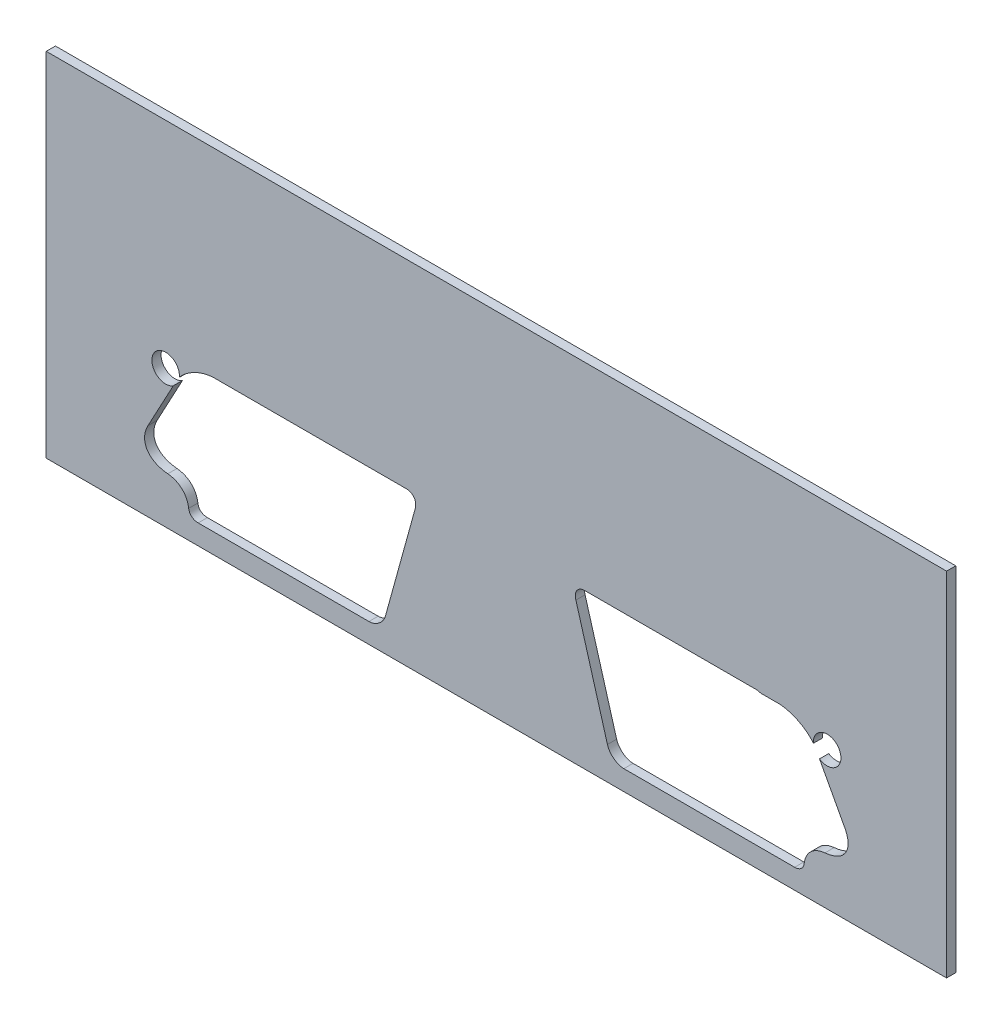
SolidWorks part; units mm, degrees
ref_plane "Спереди" through (0, 0, 0) normal (0, 0, 1) x (1, 0, 0)
ref_plane "Сверху" through (0, 0, 0) normal (0, 1, 0) x (1, 0, 0)
ref_plane "Справа" through (0, 0, 0) normal (1, 0, 0) x (0, 0, -1)
sketch "Эскиз1" plane through (0, 0, 0) normal (0, 0, 1) x (1, 0, 0)
  line L1 (-49, 5.8392) -> (-49, -22.5167)
  line L2 (-49, -22.5167) -> (49, -22.5167)
  line L3 (49, 5.8392) -> (49, -22.5167)
  line L6 (49, 26.4822) -> (49, 5.1962) construction
  line L8 (-49, 5.8392) -> (-49, 15.8392)
  line L9 (-49, 15.8392) -> (49, 15.8392)
  line L10 (49, 5.8392) -> (49, 15.8392)
extrude "Бобышка-Вытянуть1" add sketch "Эскиз1" along normal blind 1
sketch "Эскиз2" plane through (0, 0, 0) normal (0, 0, -1) x (-1, 0, 0)
  line L0 (27.2261, -9.1221) -> (15.7399, -9.1221)
  line L1 (14.9178, -10.1567) -> (17.4421, -18.9309)
  line L2 (19.1226, -20.331) -> (30.8268, -20.331)
  line L3 (31.6433, -19.2954) -> (29.101, -10.4886)
  line L4 (0, 0) -> (0, -19.7017) construction
  line L5 (-31.6433, -19.2954) -> (-29.101, -10.4886)
  line L6 (-19.1226, -20.331) -> (-30.8268, -20.331)
  line L7 (-14.9178, -10.1567) -> (-17.4421, -18.9309)
  line L8 (-27.2261, -9.1221) -> (-15.7399, -9.1221)
  arc A0 (15.7399, -9.1221) -> (14.9178, -10.1567) centre (15.8146, -10.0254) ccw
  arc A1 (17.4421, -18.9309) -> (19.1226, -20.331) centre (19.2232, -18.5017) ccw
  arc A2 (30.8268, -20.331) -> (31.6433, -19.2954) centre (30.7494, -19.4304) ccw
  arc A3 (29.101, -10.4886) -> (27.2261, -9.1221) centre (27.3312, -10.9473) ccw
  arc A4 (-29.101, -10.4886) -> (-27.2261, -9.1221) centre (-27.3312, -10.9473) cw
  arc A5 (-30.8268, -20.331) -> (-31.6433, -19.2954) centre (-30.7494, -19.4304) cw
  arc A6 (-17.4421, -18.9309) -> (-19.1226, -20.331) centre (-19.2232, -18.5017) cw
  arc A7 (-15.7399, -9.1221) -> (-14.9178, -10.1567) centre (-15.8146, -10.0254) cw
extrude "Вырез-Вытянуть4" cut sketch "Эскиз2" against normal through all
sketch "Эскиз4" plane through (0, 0, 0) normal (0, 0, -1) x (-1, 0, 0)
  circle A0 centre (36, -7.525) radius 1.5
  circle A1 centre (-36, -7.525) radius 1.5
extrude "Вырез-Вытянуть5" cut sketch "Эскиз4" against normal through all
sketch "Sketch3" plane through (0, 0, 1) normal (0, 0, 1) x (1, 0, 0)
  line L4 (-35.1709, -8.775) -> (-37.9251, -13.9067)
  line L5 (8.6523, -7.0681) -> (12.0857, -18.9615)
  line L6 (28.2287, -5.6825) -> (9.638, -5.6825)
  line L7 (30.6309, -5.7832) -> (28.7783, -5.7839)
  line L8 (37.9106, -13.8798) -> (35.1709, -8.775)
  line L9 (13.8713, -20.3472) -> (32.462, -20.3472)
  line L10 (8.6523, -7.0681) -> (12.0857, -18.9615)
  line L11 (28.2287, -5.6825) -> (9.638, -5.6825)
  line L12 (30.6309, -5.7832) -> (28.7783, -5.7839)
  line L13 (37.9106, -13.8798) -> (35.1709, -8.775)
  line L14 (13.8713, -20.3472) -> (32.462, -20.3472)
  line L15 (-9.8219, -5.7989) -> (-30.645, -5.807)
  line L16 (-12.0807, -18.9439) -> (-8.8308, -7.1669)
  line L17 (-32.462, -20.3472) -> (-13.8713, -20.3472)
  line L18 (-35.1709, -8.775) -> (-37.9251, -13.9067)
  line L19 (-9.8219, -5.7989) -> (-30.645, -5.807)
  line L20 (-12.0807, -18.9439) -> (-8.8308, -7.1669)
  line L21 (-32.462, -20.3472) -> (-13.8713, -20.3472)
  arc A2 (34.5043, -7.6389) -> (34.5716, -7.9829) centre (36, -7.525) ccw
  arc A3 (34.5716, -7.9829) -> (35.1709, -8.775) centre (36, -7.525) ccw
  arc A4 (34.5043, -7.6389) -> (34.5716, -7.9829) centre (36, -7.525) ccw
  arc A5 (34.5716, -7.9829) -> (35.1709, -8.775) centre (36, -7.525) ccw
  arc A6 (-35.1709, -8.775) -> (-34.5791, -8.0058) centre (-36, -7.525) ccw
  arc A7 (-34.5791, -8.0058) -> (-34.5051, -7.6482) centre (-36, -7.525) ccw
  arc A8 (-35.1709, -8.775) -> (-34.5791, -8.0058) centre (-36, -7.525) ccw
  arc A9 (-34.5791, -8.0058) -> (-34.5051, -7.6482) centre (-36, -7.525) ccw
  ellipse E5 centre (10.038, -7.0681) end of major axis (8.8285, -6.0207) minor radius 1.2 (9.638, -5.6825) -> (8.6523, -7.0681) ccw
  ellipse E6 centre (28.6287, -7.0681) end of major axis (27.4192, -6.0207) minor radius 1.2 (28.7783, -5.7839) -> (28.2287, -5.6825) ccw
  ellipse E7 centre (31.8702, -8.0919) end of major axis (28.7995, -6.6629) minor radius 2 (34.5043, -7.6389) -> (30.6309, -5.7832) ccw
  ellipse E8 centre (32.062, -18.9615) end of major axis (30.8525, -17.9141) minor radius 1.2 (32.462, -20.3472) -> (33.4962, -19.4843) ccw
  ellipse E9 centre (13.4713, -18.9615) end of major axis (12.2618, -17.9141) minor radius 1.2 (12.0857, -18.9615) -> (13.8713, -20.3472) ccw
  ellipse E10 centre (10.038, -7.0681) end of major axis (8.8285, -6.0207) minor radius 1.2 (9.638, -5.6825) -> (8.6523, -7.0681) ccw
  ellipse E11 centre (28.6287, -7.0681) end of major axis (27.4192, -6.0207) minor radius 1.2 (28.7783, -5.7839) -> (28.2287, -5.6825) ccw
  ellipse E12 centre (31.8702, -8.0919) end of major axis (28.7995, -6.6629) minor radius 2 (34.5043, -7.6389) -> (30.6309, -5.7832) ccw
  ellipse E13 centre (32.062, -18.9615) end of major axis (30.8525, -17.9141) minor radius 1.2 (32.462, -20.3472) -> (33.4962, -19.4843) ccw
  ellipse E14 centre (13.4713, -18.9615) end of major axis (12.2618, -17.9141) minor radius 1.2 (12.0857, -18.9615) -> (13.8713, -20.3472) ccw
  ellipse E15 centre (-31.8835, -8.1166) end of major axis (-28.8122, -6.6856) minor radius 2 (-30.645, -5.807) -> (-34.5051, -7.6482) ccw
  ellipse E16 centre (-10.2214, -7.1846) end of major axis (-9.0119, -6.1371) minor radius 1.2 (-8.8308, -7.1669) -> (-9.8219, -5.7989) ccw
  ellipse E17 centre (-13.4713, -18.9615) end of major axis (-12.2618, -17.9141) minor radius 1.2 (-13.8713, -20.3472) -> (-12.0807, -18.9439) ccw
  ellipse E18 centre (-32.062, -18.9615) end of major axis (-30.8525, -17.9141) minor radius 1.2 (-33.4952, -19.4922) -> (-32.462, -20.3472) ccw
  ellipse E19 centre (-37.0781, -20.8189) end of major axis (-34.0544, -18.2003) minor radius 3 (-33.4952, -19.4922) -> (-35.7663, -17.3693) ccw
  ellipse E20 centre (-31.8835, -8.1166) end of major axis (-28.8122, -6.6856) minor radius 2 (-30.645, -5.807) -> (-34.5051, -7.6482) ccw
  ellipse E21 centre (-10.2214, -7.1846) end of major axis (-9.0119, -6.1371) minor radius 1.2 (-8.8308, -7.1669) -> (-9.8219, -5.7989) ccw
  ellipse E22 centre (-13.4713, -18.9615) end of major axis (-12.2618, -17.9141) minor radius 1.2 (-13.8713, -20.3472) -> (-12.0807, -18.9439) ccw
  ellipse E23 centre (-32.062, -18.9615) end of major axis (-30.8525, -17.9141) minor radius 1.2 (-33.4952, -19.4922) -> (-32.462, -20.3472) ccw
  ellipse E24 centre (-37.0781, -20.8189) end of major axis (-34.0544, -18.2003) minor radius 3 (-33.4952, -19.4922) -> (-35.7663, -17.3693) ccw
  spline S1 degree 3 poles (-3612.3196, -1806.8838) (141.1066, -20.6987) (-32.5994, 3.1691) (-38.2359, -14.6873) (-38.2784, -14.8959) (-38.2974, -15.2122) (-38.2963, -15.3175) (-38.2774, -15.5276) (-38.2593, -15.6333) (-38.206, -15.8369) (-38.1708, -15.9356) (-38.0829, -16.1267) (-38.0295, -16.2198) (-37.8491, -16.4795) (-37.6989, -16.6311) (-37.3628, -16.8865) (-37.1797, -16.9895) (-17.2345, -25.642) (53.9483, 176.5986) (-943.5135, -3912.4154) knots -10.923116 -10.923116 -10.923116 -10.923116 0.125 0.125 0.25 0.25 0.3125 0.3125 0.375 0.375 0.4375 0.4375 0.5 0.5 0.625 0.625 0.75 0.75 13.437928 13.437928 13.437928 13.437928 only from (-37.9251, -13.9067) to (-35.7663, -17.3693)
  spline S2 degree 3 poles (2061.9964, -3465.9377) (-69.0178, 170.9177) (17.3944, -25.618) (37.1704, -16.959) (37.355, -16.8543) (37.6875, -16.5998) (37.8383, -16.4466) (38.0766, -16.1015) (38.1662, -15.9056) (38.2715, -15.4997) (38.2888, -15.2855) (38.2633, -14.8675) (38.2207, -14.6579) (31.82, 5.5764) (-180.6478, -51.2528) (3762.9572, 1441.6708) knots -12.455389 -12.455389 -12.455389 -12.455389 0.25 0.25 0.375 0.375 0.5 0.5 0.625 0.625 0.75 0.75 0.875 0.875 13.404708 13.404708 13.404708 13.404708 only from (35.7615, -17.3421) to (37.9106, -13.8798)
  spline S3 degree 3 poles (203.5774, 3973.3026) (187.7595, -140.5035) (26.2256, -34.1242) (33.8533, -18.4172) (34.0253, -18.1839) (34.4362, -17.8036) (34.6819, -17.6499) (51.4194, -10.709) (148.6693, -173.0193) (-3938.8197, 407.6381) knots -15.007963 -15.007963 -15.007963 -15.007963 0.25 0.25 0.5 0.5 0.75 0.75 16.651429 16.651429 16.651429 16.651429 only from (33.4962, -19.4843) to (35.7615, -17.3421)
  spline S4 degree 3 poles (35.7615, -17.3421) (36.1812, -17.3014) (36.5924, -17.2121) (37.1704, -16.959) (37.355, -16.8543) (37.6875, -16.5998) (37.8383, -16.4466) (38.0766, -16.1015) (38.1662, -15.9056) (38.2715, -15.4997) (38.2888, -15.2855) (38.2633, -14.8675) (38.2207, -14.6579) (38.0943, -14.2582) (38.0105, -14.066) (37.9106, -13.8798) knots 0 0 0 0 0.25 0.25 0.375 0.375 0.5 0.5 0.625 0.625 0.75 0.75 0.875 0.875 1 1 1 1
  spline S5 degree 3 poles (33.4962, -19.4843) (33.5297, -19.2012) (33.6073, -18.9236) (33.8533, -18.4172) (34.0253, -18.1839) (34.4362, -17.8036) (34.6819, -17.6499) (35.2, -17.4351) (35.4791, -17.3694) (35.7615, -17.3421) knots 0 0 0 0 0.25 0.25 0.5 0.5 0.75 0.75 1 1 1 1
  spline S6 degree 3 poles (-37.9251, -13.9067) (-38.0252, -14.0933) (-38.1098, -14.2878) (-38.2359, -14.6873) (-38.2784, -14.8959) (-38.2974, -15.2122) (-38.2963, -15.3175) (-38.2774, -15.5276) (-38.2593, -15.6333) (-38.206, -15.8369) (-38.1708, -15.9356) (-38.0829, -16.1267) (-38.0295, -16.2198) (-37.8491, -16.4795) (-37.6989, -16.6311) (-37.3628, -16.8865) (-37.1797, -16.9895) (-36.5959, -17.2427) (-36.1868, -17.3297) (-35.7663, -17.3693) knots 0 0 0 0 0.125 0.125 0.25 0.25 0.3125 0.3125 0.375 0.375 0.4375 0.4375 0.5 0.5 0.625 0.625 0.75 0.75 1 1 1 1
  dimension "D1" = 0
  dimension "D2" = 0
extrude "Cut-Extrude1" cut sketch "Sketch3" against normal up to surface (1 mm away) up to face at (-37.5, -7.525, 0)
sketch "Sketch5" plane through (0, 0, 1) normal (0, 0, 1) x (1, 0, 0)
  line L0 (-49, 7.8392) -> (49, 7.8392) construction
  line L1 (-49, 15.8392) -> (-49, -22.5167) construction
  line L2 (49, -22.5167) -> (49, 15.8392) construction
  line L3 (49, 15.8392) -> (-49, 15.8392) construction
  dimension "D1" = 8
